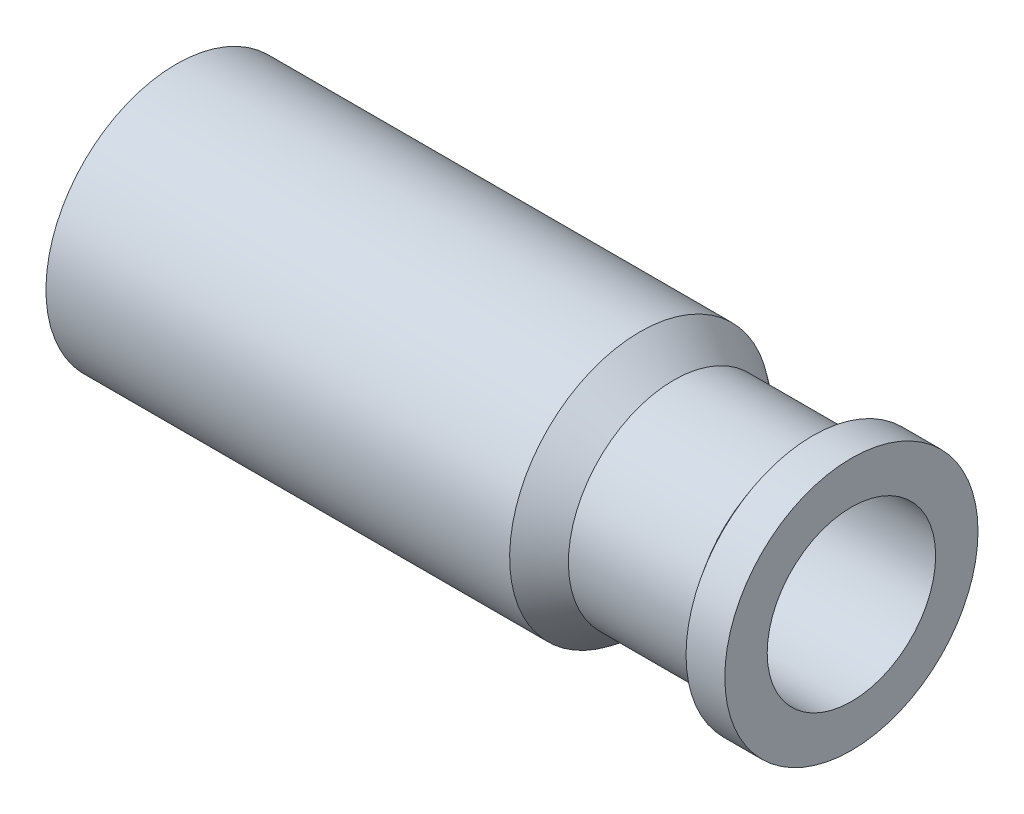
SolidWorks part; units mm, degrees
ref_plane "Front Plane" through (0, 0, 0) normal (0, 0, 1) x (1, 0, 0)
ref_plane "Top Plane" through (0, 0, 0) normal (0, 1, 0) x (1, 0, 0)
ref_plane "Right Plane" through (0, 0, 0) normal (1, 0, 0) x (0, 0, -1)
sketch "Sketch1" plane through (0, 0, 0) normal (0, 0, 1) x (1, 0, 0)
  line L1 (107.503, -15.9109) -> (117.7152, -23.3861)
  line L2 (117.7152, -23.3861) -> (154.8187, -23.3861)
  line L3 (154.8187, -23.3861) -> (159.4668, -17.0361)
  line L4 (159.4668, -17.0361) -> (171.1455, -17.0361)
  line L5 (171.1455, -17.0361) -> (171.1455, -55.1361)
  line L6 (171.1455, -55.1361) -> (-31.8619, -55.1361) construction
  line L8 (-32.0545, -55.1361) -> (171.1455, -55.1361)
  line L9 (107.503, -15.9109) -> (-32.0545, -15.9109)
  line L10 (-32.0545, -15.9109) -> (-32.0545, -55.1361)
  point P0 (154.8187, -23.3861)
  dimension "D1" = 38.1
  dimension "D3" = 31.75
  dimension "D4" = 203.2
revolve "Revolve1" add sketch "Sketch1" angle 360 about L6
sketch "Sketch4" plane through (171.1455, 0, 0) normal (1, 0, 0) x (0, 0, -1)
  circle A0 centre (0, -55.1361) radius 25.3501
extrude "Cut-Extrude1" cut sketch "Sketch4" against normal blind 190.5
